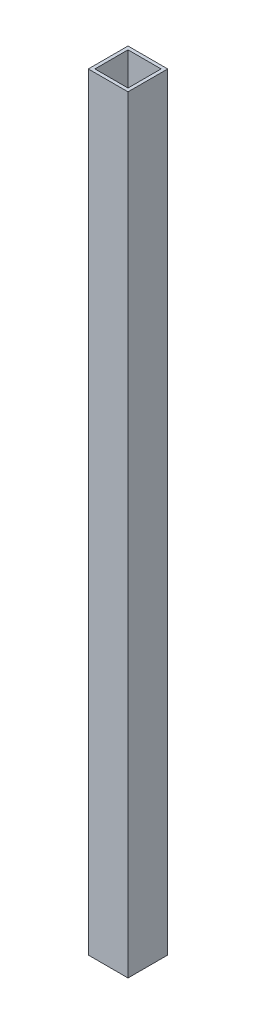
SolidWorks part; units mm, degrees
ref_plane "Front" through (0, 0, 0) normal (0, 0, 1) x (1, 0, 0)
ref_plane "Top" through (0, 0, 0) normal (0, 1, 0) x (1, 0, 0)
ref_plane "Right" through (0, 0, 0) normal (1, 0, 0) x (0, 0, -1)
sketch "Sketch1" plane through (0, 0, 0) normal (0, 1, 0) x (1, 0, 0)
  line L1 (0, 0) -> (19.05, 0)
  line L2 (0, 0) -> (0, 19.05)
  line L3 (0, 19.05) -> (19.05, 19.05)
  line L4 (19.05, 0) -> (19.05, 19.05)
  line L5 (0, 0) -> (19.05, 19.05) construction
  line L6 (0, 19.05) -> (19.05, 0) construction
  line L7 (1.5875, 1.5875) -> (17.4625, 1.5875)
  line L8 (1.5875, 1.5875) -> (1.5875, 17.4625)
  line L9 (1.5875, 17.4625) -> (17.4625, 17.4625)
  line L10 (17.4625, 1.5875) -> (17.4625, 17.4625)
  line L11 (1.5875, 1.5875) -> (17.4625, 17.4625) construction
  line L12 (1.5875, 17.4625) -> (17.4625, 1.5875) construction
  point P4 (9.525, 9.525)
  point P5 (9.525, 9.525)
  dimension "D1" = 1.5875
  dimension "D2" = 1.5875
  dimension "D3" = 19.05
extrude "Boss-Extrude1" add sketch "Sketch1" along normal blind 368.3
